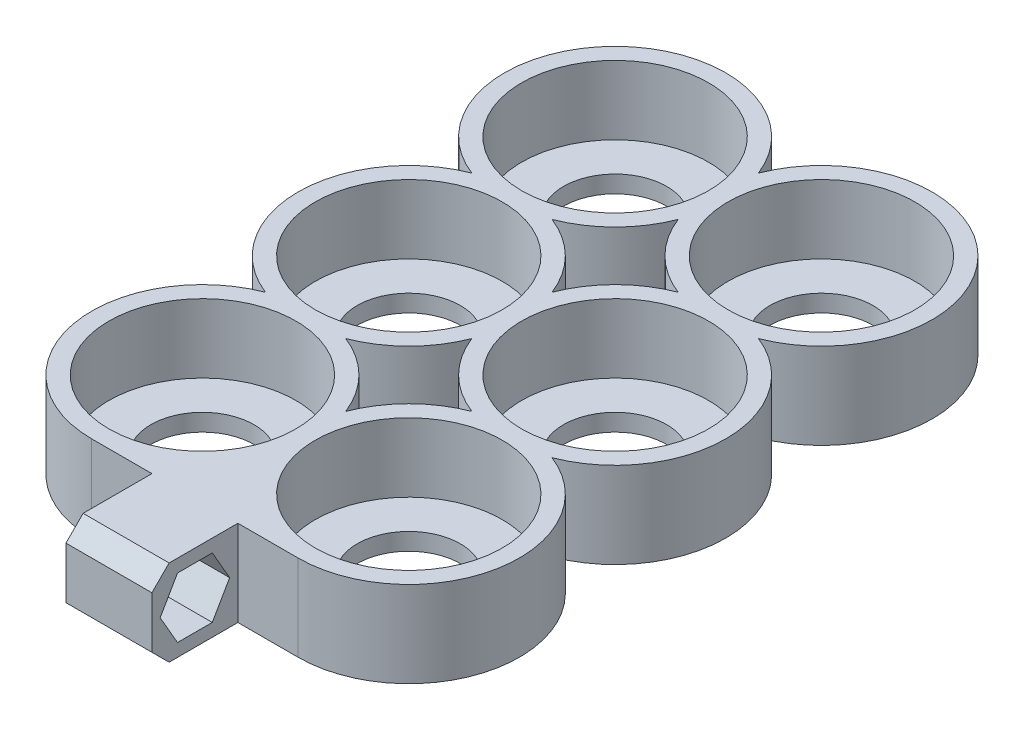
SolidWorks part; units mm, degrees
ref_plane "Front Plane" through (0, 0, 0) normal (0, 0, 1) x (1, 0, 0)
ref_plane "Top Plane" through (0, 0, 0) normal (0, 1, 0) x (1, 0, 0)
ref_plane "Right Plane" through (0, 0, 0) normal (1, 0, 0) x (0, 0, -1)
sketch "Sketch1" plane through (0, 0, 0) normal (1, 0, 0) x (0, 0, -1)
  line L0 (0, 27.0772) -> (0, -22.0037) construction
  line L1 (-12.875, 5) -> (-12.875, -5)
  line L2 (-12.875, -5) -> (-6, -5)
  line L3 (-6, -5) -> (-6, -3)
  line L4 (-6, -3) -> (-10.875, -3)
  line L5 (-10.875, -3) -> (-10.875, 5)
  line L6 (-10.875, 5) -> (-12.875, 5)
  point P5 (-12.875, 0)
  dimension "D1" = 10
  dimension "D2" = 2
  dimension "D3" = 21.75
  dimension "D4" = 12
  dimension "D5" = 2
revolve "Revolve1" add sketch "Sketch1" angle 360 about L0
sketch "Sketch2" plane through (0, -5, 0) normal (0, -1, 0) x (1, 0, 0)
  line L0 (0, 12.1827) -> (0, -11.4982) construction
pattern_linear "LPattern1" count 3 spacing 24 along (0, 0, -1) of "Revolve1"
sketch "Sketch3" plane through (0, -5, 0) normal (0, -1, 0) x (1, 0, 0)
  line L0 (-17.2986, 0) -> (17.8169, 0) construction
pattern_linear "LPattern2" count 2 spacing 24 along (1, 0, 0) of "Revolve1", "LPattern1"
ref_plane "Plane1" through (0, 0, 12.875) normal (0, 0, 1) x (1, 0, 0)
sketch "Sketch4" plane through (0, 0, 12.875) normal (0, 0, 1) x (1, 0, 0)
  line L0 (12, 5) -> (12, -5) construction
  line L1 (12, 5) -> (-12.875, 5) construction
  line L2 (24, -5) -> (0, -5)
  line L3 (24, -5) -> (24, 5)
  line L4 (24, 5) -> (0, 5)
  line L5 (0, -5) -> (0, 5)
  line L6 (24, -5) -> (0, 5) construction
  line L7 (24, 5) -> (0, -5) construction
  point P4 (12, 0)
  dimension "D1" = 24
extrude "Boss-Extrude1" add sketch "Sketch4" against normal up to next
sketch "Sketch5" plane through (0, 0, 12.875) normal (0, 0, 1) x (1, 0, 0)
  line L0 (12, 5) -> (12, -5) construction
  line L1 (24, 5) -> (0, 5) construction
  line L2 (0, -5) -> (24, -5) construction
  line L8 (17, -5) -> (7, -5)
  line L9 (17, -5) -> (17, 5)
  line L10 (17, 5) -> (7, 5)
  line L11 (7, -5) -> (7, 5)
  line L12 (17, -5) -> (7, 5) construction
  line L13 (17, 5) -> (7, -5) construction
  point P6 (12, 0)
  point P7 (12, 0)
  dimension "D1" = 10
  dimension "D2" = 10
extrude "Boss-Extrude2" add sketch "Sketch5" along normal blind 10
sketch "Sketch8" plane through (7, 0, 0) normal (-1, 0, 0) x (0, 0, 1)
  line L0 (12.875, 0) -> (22.875, 0) construction
  line L1 (12.875, -3.3) -> (12.875, 3.3) construction
  line L2 (22.875, 5) -> (22.875, -5) construction
  line L3 (17.875, 5) -> (17.875, -5) construction
  line L4 (22.875, 5) -> (12.875, 5) construction
  line L5 (22.875, -5) -> (12.875, -5) construction
  line L7 (19.8957, -3.5) -> (21.9165, 0)
  line L8 (21.9165, 0) -> (19.8957, 3.5)
  line L9 (19.8957, 3.5) -> (15.8543, 3.5)
  line L10 (15.8543, 3.5) -> (13.8335, 0)
  line L11 (13.8335, 0) -> (15.8543, -3.5)
  line L12 (15.8543, -3.5) -> (19.8957, -3.5)
  circle A0 centre (17.875, 0) radius 3.5 construction
  dimension "D1" = 7
extrude "Cut-Extrude1" cut sketch "Sketch8" against normal up to surface (10 mm away) up to face at (17, 0, 17.875)
chamfer "Chamfer3" distance 2 angle 45 2 edges at (12, -5, 22.875) (12, 5, 22.875)
ref_plane "Plane3" through (0, 0, -24) normal (0, 0, 1) x (1, 0, 0)
